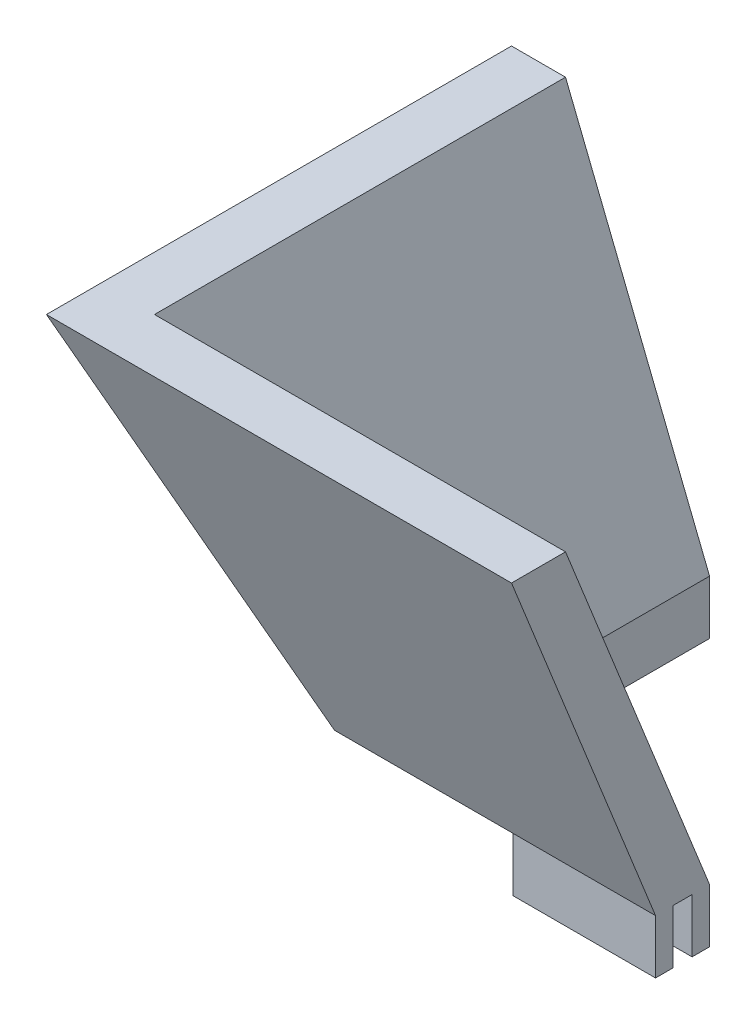
SolidWorks part; units mm, degrees
ref_plane "Front Plane" through (0, 0, 0) normal (0, 0, 1) x (1, 0, 0)
ref_plane "Top Plane" through (0, 0, 0) normal (0, 1, 0) x (1, 0, 0)
ref_plane "Right Plane" through (0, 0, 0) normal (1, 0, 0) x (0, 0, -1)
sketch "Sketch1" plane through (0, 0, 0) normal (0, 1, 0) x (1, 0, 0)
  line L1 (0, 0) -> (227.33, 0)
  line L2 (0, 0) -> (0, 225.552)
  line L3 (0, 225.552) -> (227.33, 225.552)
  line L4 (227.33, 0) -> (227.33, 225.552)
  dimension "D1" = 227.33
  dimension "D2" = 225.552
ref_plane "Plane1" through (0, 127, 0) normal (0, 1, 0) x (1, 0, 0)
sketch "Sketch2" plane through (0, 127, 0) normal (0, 1, 0) x (1, 0, 0)
  line L8 (-50.8, -50.8) -> (278.13, -50.8)
  line L9 (278.13, -50.8) -> (278.13, 276.352)
  line L10 (278.13, 276.352) -> (-50.8, 276.352)
  line L11 (-50.8, 276.352) -> (-50.8, -50.8)
  line L12 (-50.8, -50.8) -> (278.13, -50.8)
  line L13 (278.13, -50.8) -> (278.13, 276.352)
  line L14 (278.13, 276.352) -> (-50.8, 276.352)
  line L15 (-50.8, 276.352) -> (-50.8, -50.8)
  dimension "D1" = 50.8
loft "Loft1" add profiles "Sketch2" section "Sketch2" section "Sketch1"
sketch "Sketch3" plane through (0, 127, 0) normal (0, 1, 0) x (1, 0, 0)
  line L8 (-31.75, 257.302) -> (-31.75, -31.75)
  line L9 (-31.75, -31.75) -> (259.08, -31.75)
  line L10 (259.08, -31.75) -> (259.08, 257.302)
  line L11 (259.08, 257.302) -> (-31.75, 257.302)
  line L12 (-31.75, 257.302) -> (-31.75, -31.75)
  line L13 (-31.75, -31.75) -> (259.08, -31.75)
  line L14 (259.08, -31.75) -> (259.08, 257.302)
  line L15 (259.08, 257.302) -> (-31.75, 257.302)
  dimension "D1" = 19.05
sketch "Sketch4" plane through (0, 0, 0) normal (0, -1, 0) x (1, 0, 0)
  line L8 (208.28, -19.05) -> (19.05, -19.05)
  line L9 (19.05, -19.05) -> (19.05, -206.502)
  line L10 (19.05, -206.502) -> (208.28, -206.502)
  line L11 (208.28, -206.502) -> (208.28, -19.05)
  line L12 (208.28, -19.05) -> (19.05, -19.05)
  line L13 (19.05, -19.05) -> (19.05, -206.502)
  line L14 (19.05, -206.502) -> (208.28, -206.502)
  line L15 (208.28, -206.502) -> (208.28, -19.05)
  dimension "D1" = 19.05
loft "Cut-Loft3" cut profiles "Sketch3" section "Sketch4" section "Sketch3"
sketch "Sketch5" plane through (0, 0, 0) normal (0, -1, 0) x (1, 0, 0)
  line L0 (0, -61.976) -> (6.1595, -61.976)
  line L5 (0, -61.976) -> (0, -163.576)
  line L6 (0, 0) -> (0, -225.552) construction
  line L7 (6.1595, -61.976) -> (6.1595, -163.576)
  line L8 (6.1595, -163.576) -> (0, -163.576)
  line L9 (19.05, -61.976) -> (19.05, -163.576)
  line L10 (19.05, -19.05) -> (19.05, -206.502) construction
  line L11 (19.05, -61.976) -> (12.8905, -61.976)
  line L12 (12.8905, -61.976) -> (12.8905, -163.576)
  line L13 (12.8905, -163.576) -> (19.05, -163.576)
  line L14 (19.05, -19.05) -> (208.28, -206.502) construction
  line L15 (164.465, -6.1595) -> (62.865, -6.1595)
  line L16 (164.465, 0) -> (62.865, 0)
  line L17 (164.465, 0) -> (164.465, -6.1595)
  line L18 (62.865, -6.1595) -> (62.865, 0)
  line L19 (164.465, -12.8905) -> (62.865, -12.8905)
  line L20 (164.465, -19.05) -> (62.865, -19.05)
  line L21 (164.465, -19.05) -> (164.465, -12.8905)
  line L22 (62.865, -12.8905) -> (62.865, -19.05)
  line L23 (220.2815, -164.465) -> (220.2815, -62.865)
  line L24 (226.441, -164.465) -> (226.441, -62.865)
  line L25 (226.441, -164.465) -> (220.2815, -164.465)
  line L26 (220.2815, -62.865) -> (226.441, -62.865)
  line L27 (213.5505, -164.465) -> (213.5505, -62.865)
  line L28 (207.391, -164.465) -> (207.391, -62.865)
  line L29 (207.391, -164.465) -> (213.5505, -164.465)
  line L30 (213.5505, -62.865) -> (207.391, -62.865)
  line L31 (61.976, -220.2815) -> (163.576, -220.2815)
  line L32 (61.976, -226.441) -> (163.576, -226.441)
  line L33 (61.976, -226.441) -> (61.976, -220.2815)
  line L34 (163.576, -220.2815) -> (163.576, -226.441)
  line L35 (61.976, -213.5505) -> (163.576, -213.5505)
  line L36 (61.976, -207.391) -> (163.576, -207.391)
  line L37 (61.976, -207.391) -> (61.976, -213.5505)
  line L38 (163.576, -213.5505) -> (163.576, -207.391)
  line L39 (0, 0) -> (227.33, 0) construction
  point P5 (0, -112.776)
  point P12 (19.05, -112.776)
  point P14 (113.665, -112.776)
  point P46 (113.2205, -113.2205)
  dimension "D1" = 101.6
  dimension "D2" = 6.731
  dimension "D3" = 4
extrude "Boss-Extrude1" add sketch "Sketch5" along normal blind 19.05
ref_plane "Plane2" through (0, 0, -113.2205) normal (0, 0, 1) x (1, 0, 0)
sketch "Sketch6" plane through (0, 0, -113.2205) normal (0, 0, 1) x (1, 0, 0)
  line L1 (278.13, 127) -> (-54.8956, 127)
  line L2 (278.13, 127) -> (278.13, -23.8217)
  line L3 (278.13, -23.8217) -> (-54.8956, -23.8217)
  line L4 (-54.8956, 127) -> (-54.8956, -23.8217)
extrude "Cut-Extrude1" cut sketch "Sketch6" against normal blind 205.486
ref_plane "Plane3" through (113.2205, 0, 0) normal (-1, 0, 0) x (0, 0, 1)
sketch "Sketch7" plane through (113.2205, 0, 0) normal (-1, 0, 0) x (0, 0, 1)
  line L1 (-116.3268, -25.7528) -> (56.5129, -25.7528)
  line L2 (-116.3268, -25.7528) -> (-116.3268, 130.244)
  line L3 (-116.3268, 130.244) -> (56.5129, 130.244)
  line L4 (56.5129, -25.7528) -> (56.5129, 130.244)
extrude "Cut-Extrude2" cut sketch "Sketch7" against normal blind 205.486
